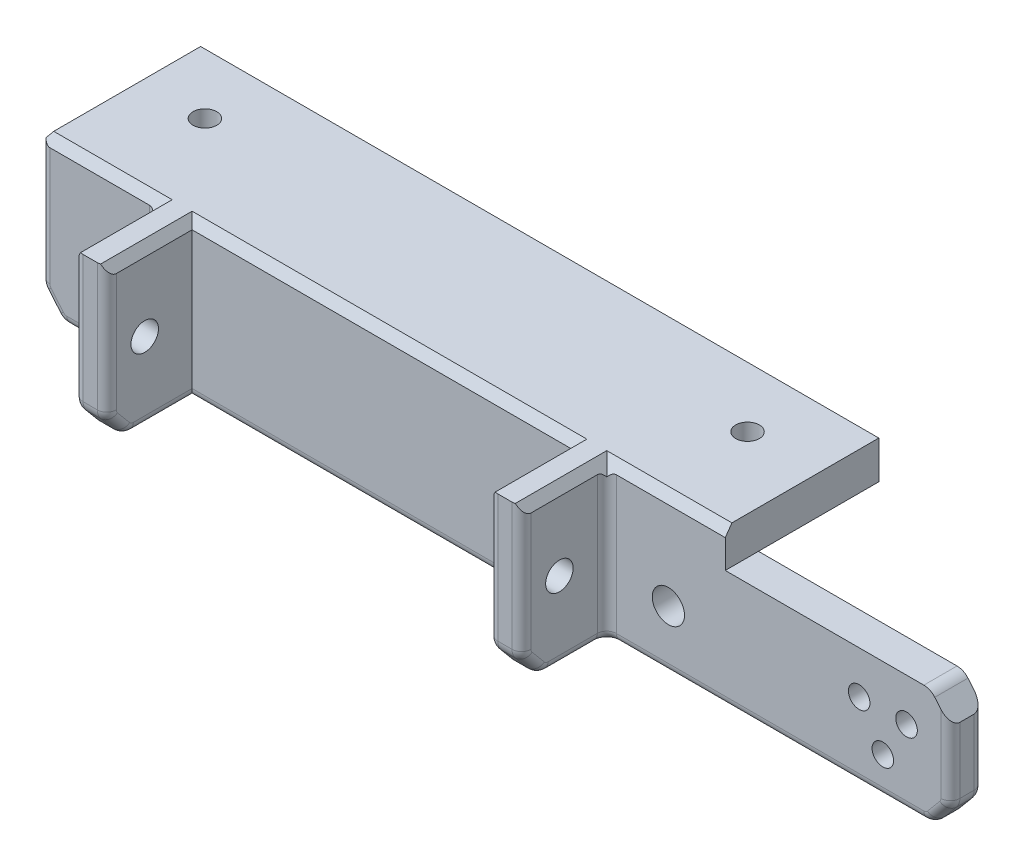
SolidWorks part; units mm, degrees
ref_plane "Front Plane" through (0, 0, 0) normal (0, 0, 1) x (1, 0, 0)
ref_plane "Top Plane" through (0, 0, 0) normal (0, 1, 0) x (1, 0, 0)
ref_plane "Right Plane" through (0, 0, 0) normal (1, 0, 0) x (0, 0, -1)
sketch "Sketch1" plane through (0, 0, 0) normal (0, 1, 0) x (1, 0, 0)
  line L1 (119.75, 0) -> (119.75, -7)
  line L2 (119.75, -7) -> (47.25, -7)
  line L3 (47.25, -7) -> (47.25, -25)
  line L4 (47.25, -25) -> (40.25, -25)
  line L5 (40.25, -25) -> (40.25, -7)
  line L6 (40.25, -7) -> (-40.25, -7)
  line L7 (-40.25, -7) -> (-40.25, -25)
  line L8 (-40.25, -25) -> (-47.25, -25)
  line L9 (-47.25, -25) -> (-47.25, -7)
  line L10 (-47.25, -7) -> (-72.25, -7)
  line L11 (-72.25, -7) -> (-72.25, 0)
  line L12 (119.75, 0) -> (-72.25, 0)
  point P14 (0, -7)
  dimension "D1" = 7
  dimension "D2" = 7
  dimension "D3" = 80.5
  dimension "D4" = 18
  dimension "D5" = 25
  dimension "D6" = 72.5
extrude "Boss-Extrude1" add sketch "Sketch1" along normal mid plane 25
sketch "Sketch2" plane through (0, 0, 7) normal (0, 0, 1) x (1, 0, 0)
  line L1 (-72.25, 12.5) -> (-72.25, -12.5) construction
  line L2 (-72.25, 0) -> (-60.25, 0) construction
  line L3 (0, -13.7502) -> (0, 13.7502) construction
  circle A0 centre (-60.25, 0) radius 3.4
  circle A2 centre (60.25, 0) radius 3.4
  dimension "D2" = 6.8
  dimension "D1" = 12
extrude "Cut-Extrude1" cut sketch "Sketch2" against normal through all
sketch "Sketch4" plane through (0, 12.5, 0) normal (0, 1, 0) x (1, 0, 0)
  line L1 (-72.25, -7) -> (-47.25, -7)
  line L2 (-72.25, -7) -> (-72.25, 25.4)
  line L3 (-72.25, 25.4) -> (72.25, 25.4)
  line L4 (72.25, -7) -> (72.25, 25.4)
  line L5 (119.75, 0) -> (-72.25, 0) construction
  line L6 (-72.25, 12.7) -> (-57.25, 12.7) construction
  line L7 (57.25, 12.7) -> (72.25, 12.7) construction
  line L8 (-40.25, -7) -> (40.25, -7)
  line L10 (-47.25, -7) -> (-47.25, -25)
  line L11 (-47.25, -25) -> (-40.25, -25)
  line L12 (-40.25, -7) -> (-40.25, -25)
  line L14 (40.25, -7) -> (40.25, -25)
  line L15 (40.25, -25) -> (47.25, -25)
  line L16 (47.25, -7) -> (47.25, -25)
  line L18 (72.25, -7) -> (47.25, -7)
  circle A0 centre (-57.25, 12.7) radius 2.5
  circle A1 centre (57.25, 12.7) radius 2.5
  dimension "D3" = 5
  dimension "D4" = 12.7
  dimension "D1" = 25.4
  dimension "D2" = 15
extrude "Boss-Extrude2" add sketch "Sketch4" along normal blind 8
sketch "Sketch3" plane through (-47.25, 0, 0) normal (-1, 0, 0) x (0, 0, 1)
  line L1 (7, 20.5) -> (7, -12.5) construction
  line L2 (25, 20.5) -> (25, -12.5) construction
  circle A0 centre (17, 4) radius 2.9
  point P8 (25, 4)
  dimension "D2" = 5.8
  dimension "D1" = 10
extrude "Cut-Extrude2" cut sketch "Sketch3" against normal through all
sketch "Sketch8" plane through (0, 0, 7) normal (0, 0, 1) x (1, 0, 0)
  line L0 (110.5, 3.5) -> (100.5, 3.5) construction
  line L1 (105.5, 3.5) -> (105.5, -4.5) construction
  line L2 (47.25, -12.5) -> (119.75, -12.5) construction
  circle A0 centre (100.5, 3.5) radius 2.275
  circle A1 centre (110.5, 3.5) radius 2.275
  circle A2 centre (105.5, -4.5) radius 2.275
  dimension "D3" = 4.55
  dimension "D1" = 10
  dimension "D2" = 8
  dimension "D4" = 105.5
  dimension "D5" = 8
extrude "Cut-Extrude4" cut sketch "Sketch8" against normal up to next
chamfer "Chamfer1" distance 5 angle 40 5 edges at (119.75, 12.5, 3.5) (119.75, -12.5, 3.5) (-72.25, -12.5, 3.5) (43.75, -12.5, 25) (-43.75, -12.5, 25)
chamfer "Chamfer3" [suppressed] distance 5 angle 40
chamfer "Chamfer4" [suppressed] distance 5 angle 40
fillet "Fillet1" radius 3 9 edges at (43.75, -7.5, 25) (-43.75, -7.5, 25) (-72.25, -7.5, 3.5) (119.75, -7.5, 3.5) (43.75, -12.5, 20.8045) (-43.75, -12.5, 20.8045) (115.5545, -12.5, 3.5) (-68.0545, -12.5, 3.5) (115.5545, 12.5, 3.5)
chamfer "Chamfer2" distance 2 angle 35 8 edges at (59.75, 20.5, 7) (47.25, 20.5, 16) (40.25, 20.5, 16) (0, 20.5, 7) (-40.25, 20.5, 16) (-47.25, 20.5, 16) (-59.75, 20.5, 7) (-72.25, 20.5, -9.2)
fillet "Fillet2" radius 2 42 edges at (-72.25, 6.046, 7) (-72.0691, -7.4341, 7) (-70.2509, -9.8824, 7) (-67.9234, -12.2189, 7) (-56.9528, -12.5, 7) (119.5691, -7.4341, 7) (117.7509, -9.8824, 7) (115.4234, -12.2189, 7) (119.75, 0.546, 0) (119.5691, -7.4341, 0) (117.7509, -9.8824, 0) (115.4234, -12.2189, 0) (-72.25, 3.046, 0) (-72.0691, -7.4341, 0) (-70.2509, -9.8824, 0) (-67.9234, -12.2189, 0) (47.25, -12.5, 13.2028) (47.25, -12.2189, 20.6734) (47.25, -9.8824, 23.0009) (47.25, -7.4341, 24.8191) (40.25, -12.5, 13.2028) (40.25, -12.2189, 20.6734) (40.25, -9.8824, 23.0009) (40.25, -7.4341, 24.8191) (-40.25, -12.5, 13.2028) (-40.25, -12.2189, 20.6734) (-40.25, -9.8824, 23.0009) (-40.25, -7.4341, 24.8191) (-47.25, -12.5, 13.2028) (-47.25, -12.2189, 20.6734) (-47.25, -9.8824, 23.0009) (-47.25, -7.4341, 24.8191) (-47.25, 6.046, 25) (47.25, 3, 7) (80.7028, -12.5, 7) (0, -12.5, 7) (23.75, -12.5, 0) (-47.25, 3, 7) (47.25, 6.046, 25) (40.25, 6.046, 25) (-40.25, 6.046, 25) (119.75, 0.546, 7)
fillet "Fillet3" [suppressed] radius 2
fillet "Fillet4" [suppressed] radius 2
chamfer "Chamfer5" [suppressed] distance 1 angle 40
